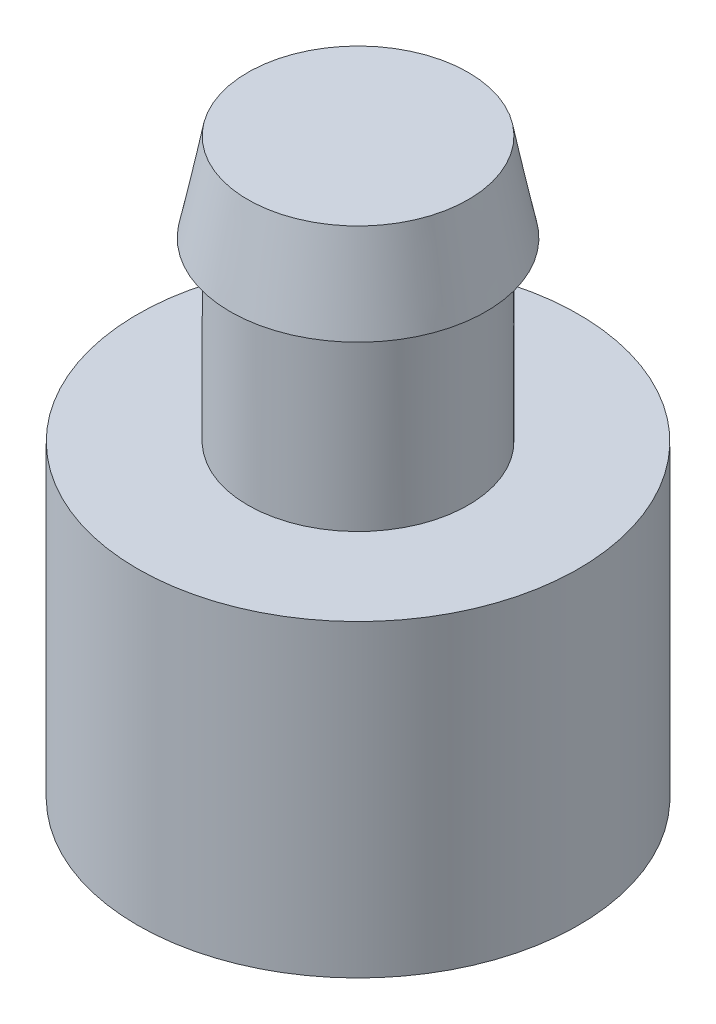
SolidWorks part; units mm, degrees
ref_plane "Front Plane" through (0, 0, 0) normal (0, 0, 1) x (1, 0, 0)
ref_plane "Top Plane" through (0, 0, 0) normal (0, 1, 0) x (1, 0, 0)
ref_plane "Right Plane" through (0, 0, 0) normal (1, 0, 0) x (0, 0, -1)
sketch "Sketch1" plane through (0, 0, 0) normal (0, 1, 0) x (1, 0, 0)
  circle A0 centre (0, 0) radius 2.5
  dimension "D1" = 5
extrude "Boss-Extrude1" add sketch "Sketch1" along normal blind 3.5
sketch "Sketch2" plane through (0, 3.5, 0) normal (0, 1, 0) x (1, 0, 0)
  circle A0 centre (0, 0) radius 1.25
  dimension "D1" = 2.5
extrude "Boss-Extrude2" add sketch "Sketch2" along normal blind 3
sketch "Sketch3" plane through (0, 0, 0) normal (0, 0, 1) x (1, 0, 0)
  line L0 (1.25, 6.5) -> (1.25, 5.5)
  line L1 (1.25, 3.5) -> (1.25, 6.5) construction
  line L2 (1.25, 5.5) -> (1.45, 5.5)
  line L3 (1.45, 5.5) -> (1.25, 6.5)
  line L4 (0, 0) -> (0, 6.5) construction
  line L5 (1.25, 6.5) -> (-1.25, 6.5) construction
  dimension "D1" = 0.2
  dimension "D2" = 1
revolve "Revolve1" add sketch "Sketch3" angle 360 about L4
